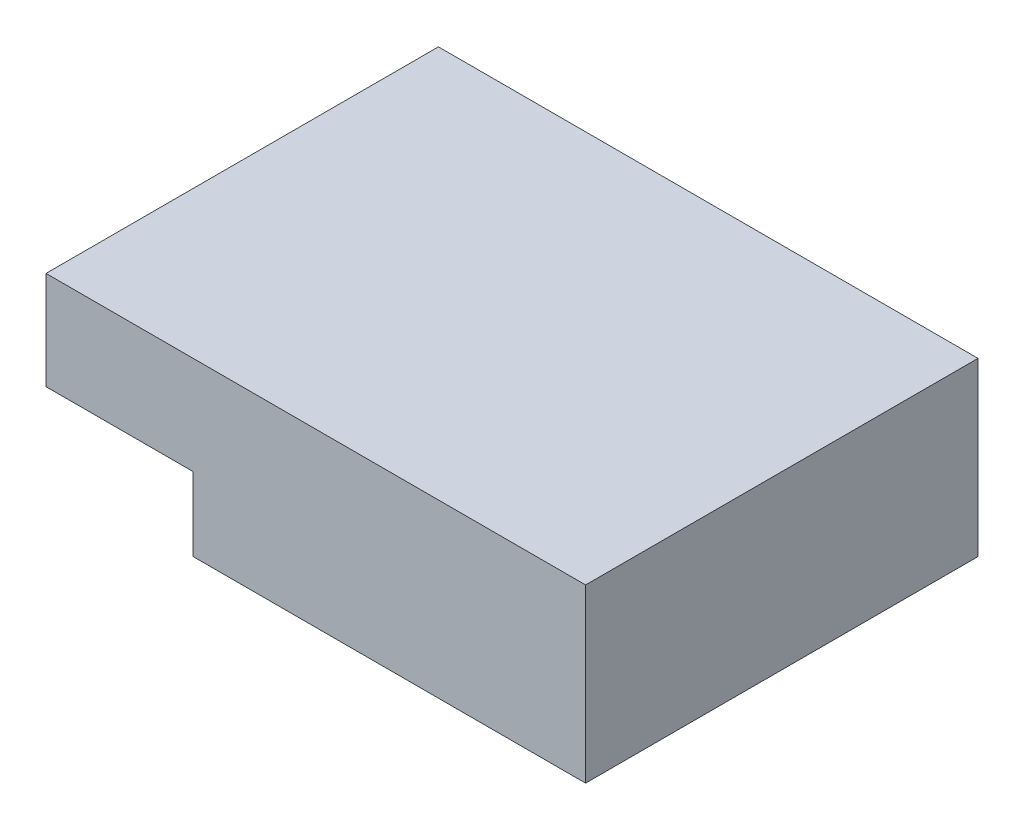
SolidWorks part; units mm, degrees
ref_plane "Front Plane" through (0, 0, 0) normal (0, 0, 1) x (1, 0, 0)
ref_plane "Top Plane" through (0, 0, 0) normal (0, 1, 0) x (1, 0, 0)
ref_plane "Right Plane" through (0, 0, 0) normal (1, 0, 0) x (0, 0, -1)
sketch "Sketch1" plane through (0, 0, 0) normal (0, 0, 1) x (1, 0, 0)
  line L0 (0, 0) -> (0, 1.5)
  line L1 (0, 1.5) -> (-3, 1.5)
  line L2 (-3, 1.5) -> (-3, 3.5)
  line L3 (-3, 3.5) -> (8, 3.5)
  line L4 (8, 3.5) -> (8, 0)
  line L5 (8, 0) -> (0, 0)
  dimension "D1" = 3
  dimension "D2" = 8
  dimension "D3" = 2
  dimension "D4" = 3.5
extrude "Boss-Extrude1" add sketch "Sketch1" along normal mid plane 8
